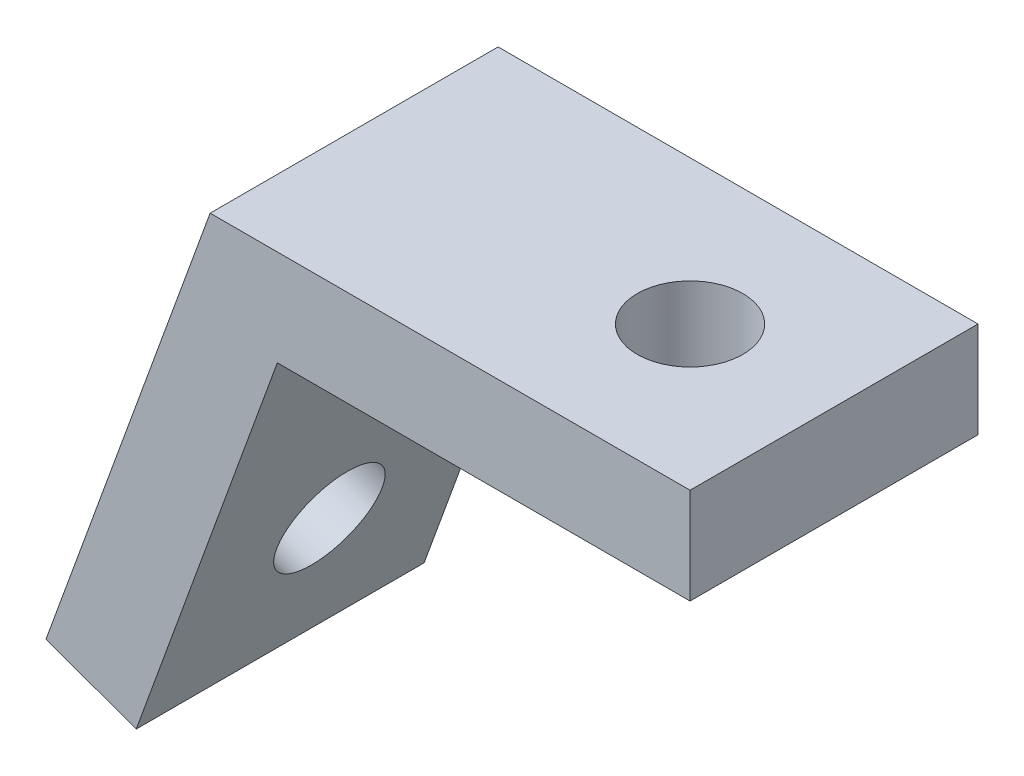
SolidWorks part; units mm, degrees
ref_plane "Front Plane" through (0, 0, 0) normal (0, 0, 1) x (1, 0, 0)
ref_plane "Top Plane" through (0, 0, 0) normal (0, 1, 0) x (1, 0, 0)
ref_plane "Right Plane" through (0, 0, 0) normal (1, 0, 0) x (0, 0, -1)
sketch "Sketch1" plane through (0, 0, 0) normal (0, 0, 1) x (1, 0, 0)
  line L0 (7.0848, 1.3689) -> (-2.9152, 1.3689)
  line L1 (-2.9152, 1.3689) -> (-6.3354, -8.028)
  line L2 (-6.3354, -8.028) -> (-4.456, -8.712)
  line L3 (-4.456, -8.712) -> (-1.5148, -0.6311)
  line L4 (-1.5148, -0.6311) -> (7.0848, -0.6311)
  line L5 (7.0848, -0.6311) -> (7.0848, 1.3689)
  dimension "D1" = 10
  dimension "D2" = 10
  dimension "D3" = 2
  dimension "D4" = 2
  dimension "D5" = 110
extrude "Boss-Extrude1" add sketch "Sketch1" along normal blind 6
sketch "Sketch2" plane through (0, 1.3689, 0) normal (0, 1, 0) x (1, 0, 0)
  line L0 (7.0848, -6) -> (7.0848, 0) construction
  line L1 (7.0848, 0) -> (-2.9152, 0) construction
  circle A0 centre (4.0848, -3) radius 1.1
  dimension "D1" = 2.2
  dimension "D2" = 3
  dimension "D3" = 3
extrude "Cut-Extrude1" cut sketch "Sketch2" against normal blind 6
sketch "Sketch3" plane through (-3.0141, 1.0971, 0) normal (-0.9397, 0.342, 0) x (0, 0, 1)
  line L0 (6, 0.2893) -> (6, -9.7107) construction
  line L1 (6, -9.7107) -> (0, -9.7107) construction
  circle A0 centre (3, -6.7107) radius 1.1
  dimension "D1" = 2.2
  dimension "D2" = 3
  dimension "D3" = 3
extrude "Cut-Extrude2" cut sketch "Sketch3" against normal blind 6
